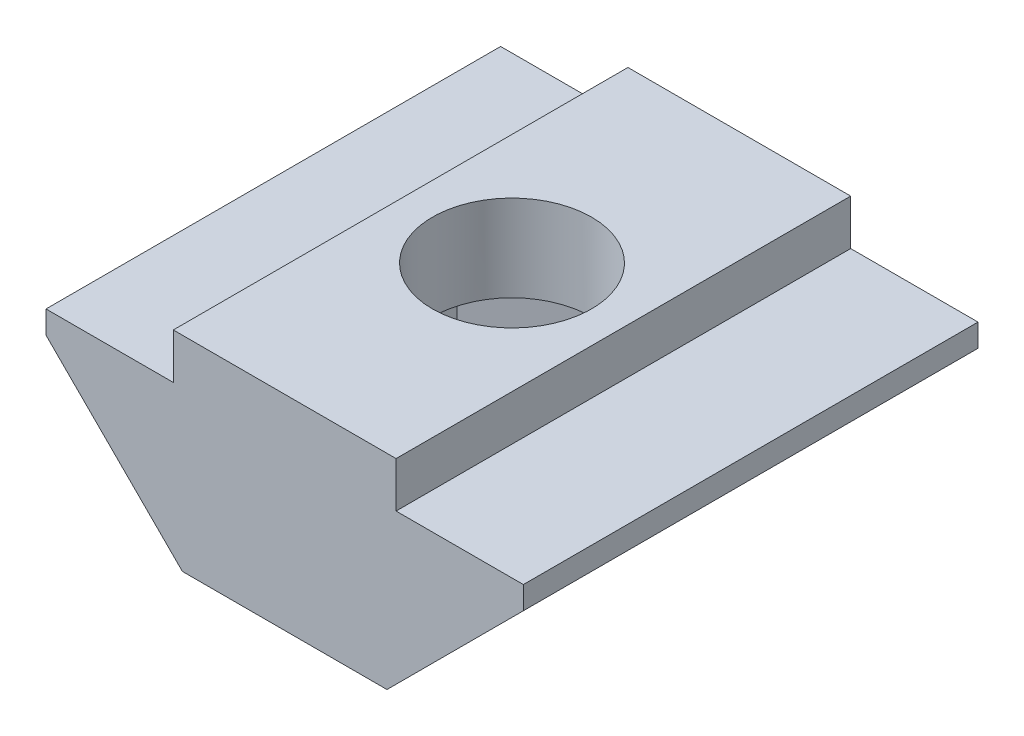
SolidWorks part; units mm, degrees
ref_plane "Plan de face" through (0, 0, 0) normal (0, 0, 1) x (1, 0, 0)
ref_plane "Plan de dessus" through (0, 0, 0) normal (0, 1, 0) x (1, 0, 0)
ref_plane "Plan de droite" through (0, 0, 0) normal (1, 0, 0) x (0, 0, -1)
sketch "Esquisse1" plane through (0, 0, 0) normal (0, 0, 1) x (1, 0, 0)
  line L0 (-2.25, 0) -> (2.25, 0)
  line L1 (2.25, 0) -> (5.25, 3)
  line L2 (5.25, 3) -> (5.25, 3.5)
  line L3 (5.25, 3.5) -> (2.45, 3.5)
  line L4 (2.45, 3.5) -> (2.45, 4.5)
  line L5 (2.45, 4.5) -> (-2.45, 4.5)
  line L6 (0, 4.5) -> (0, 0) construction
  line L7 (-2.45, 3.5) -> (-2.45, 4.5)
  line L8 (-5.25, 3.5) -> (-2.45, 3.5)
  line L9 (-5.25, 3) -> (-5.25, 3.5)
  line L10 (-2.25, 0) -> (-5.25, 3)
  dimension "D1" = 10.5
  dimension "D2" = 3.5
  dimension "D3" = 4.9
  dimension "D4" = 1
  dimension "D5" = 135
  dimension "D6" = 3
extrude "Boss.-Extru.1" add sketch "Esquisse1" along normal blind 100
sketch "Esquisse2" plane through (0, 4.5, 0) normal (0, 1, 0) x (1, 0, 0)
  line L0 (0, -100) -> (0, 0) construction
  line L1 (2.45, -100) -> (-2.45, -100) construction
  line L2 (0, -50) -> (-5.25, -50) construction
  line L3 (-5.25, -100) -> (-5.25, 0) construction
  circle A0 centre (0, -50) radius 1.75
  point P11 (0, -50.8241)
  point P13 (0, -63.5567)
  dimension "D2" = 3.5
extrude "Enlèv. mat.-Extru.1" cut sketch "Esquisse2" against normal through all
sketch "Esquisse3" plane through (0, 4.5, 0) normal (0, 1, 0) x (1, 0, 0)
  line L1 (-5.25, -50) -> (5.25, -50) construction
  line L2 (-5.25, -100) -> (-5.25, 0) construction
  line L3 (5.25, -100) -> (5.25, 0) construction
  line L4 (-5.25, -100) -> (5.25, -100)
  line L6 (-5.25, -45) -> (5.25, -45)
  line L7 (-5.25, -45) -> (-5.25, 0)
  line L8 (-5.25, 0) -> (5.25, 0)
  line L9 (5.25, -45) -> (5.25, 0)
  line L10 (5.25, -55) -> (5.25, -100)
  line L11 (-5.25, -55) -> (5.25, -55)
  line L12 (-5.25, -55) -> (-5.25, -100)
  line L13 (0, -50) -> (0, -45) construction
  dimension "D1" = 5
extrude "Enlèv. mat.-Extru.2" cut sketch "Esquisse3" against normal through all both and the other way through all
sketch "Esquisse4" plane through (0, 0, 0) normal (0, -1, 0) x (1, 0, 0)
  line L1 (2.85, 48.3546) -> (2.85, 51.6454)
  line L2 (2.85, 51.6454) -> (0, 53.2909)
  line L3 (0, 53.2909) -> (-2.85, 51.6454)
  line L4 (-2.85, 51.6454) -> (-2.85, 48.3546)
  line L5 (-2.85, 48.3546) -> (0, 46.7091)
  line L6 (0, 46.7091) -> (2.85, 48.3546)
  circle A0 centre (0, 50) radius 2.85 construction
  dimension "D1" = 5.7
extrude "Enlèv. mat.-Extru.3" cut sketch "Esquisse4" against normal blind 2.6
